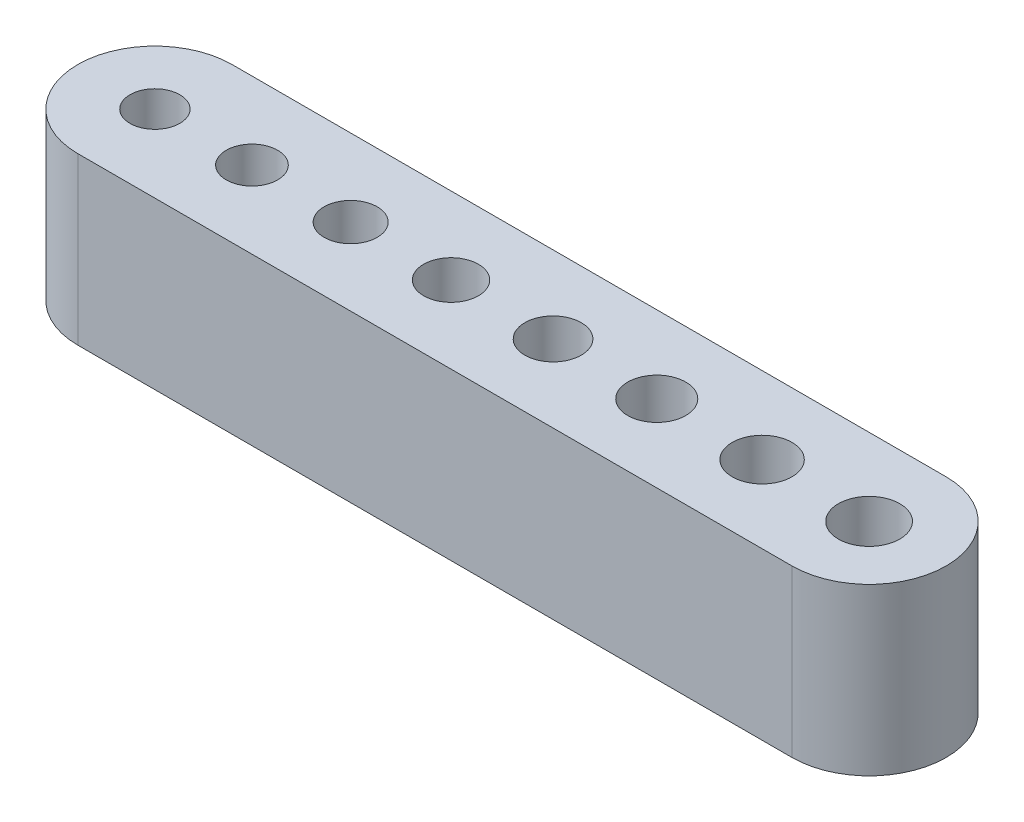
SolidWorks part; units mm, degrees
ref_plane "Front Plane" through (0, 0, 0) normal (0, 0, 1) x (1, 0, 0)
ref_plane "Top Plane" through (0, 0, 0) normal (0, 1, 0) x (1, 0, 0)
ref_plane "Right Plane" through (0, 0, 0) normal (1, 0, 0) x (0, 0, -1)
sketch "Sketch1" plane through (0, 0, 0) normal (0, 1, 0) x (1, 0, 0)
  line L0 (-21.525, 0) -> (21.525, 0) construction
  line L1 (-21.525, 4.65) -> (21.525, 4.65)
  line L2 (-21.525, -4.65) -> (21.525, -4.65)
  line L3 (-20.025, 0) -> (-17.225, 0) construction
  line L4 (-14.125, 0) -> (-11.325, 0) construction
  line L5 (-8.125, 0) -> (-5.325, 0) construction
  line L6 (-2.025, 0) -> (0.775, 0) construction
  line L7 (4.175, 0) -> (6.975, 0) construction
  line L8 (23.375, 0) -> (26.175, 0) construction
  line L10 (10.475, 0) -> (13.275, 0) construction
  line L11 (16.875, 0) -> (19.675, 0) construction
  arc A0 (-21.525, 4.65) -> (-21.525, -4.65) centre (-21.525, 0) ccw
  arc A1 (21.525, -4.65) -> (21.525, 4.65) centre (21.525, 0) ccw
  circle A2 centre (-21.525, 0) radius 1.5
  circle A3 centre (-15.675, 0) radius 1.55
  circle A4 centre (-9.725, 0) radius 1.6
  circle A5 centre (-3.675, 0) radius 1.65
  circle A6 centre (2.475, 0) radius 1.7
  circle A7 centre (21.525, 0) radius 1.85
  circle A8 centre (8.725, 0) radius 1.75
  circle A9 centre (15.075, 0) radius 1.8
  point P2 (0, 0)
  dimension "D1" = 3
  dimension "D2" = 3.1
  dimension "D3" = 3.2
  dimension "D4" = 3.3
  dimension "D5" = 3.4
  dimension "D6" = 3.7
  dimension "D7" = 3.5
  dimension "D8" = 3.6
  dimension "D9" = 2.8
extrude "Boss-Extrude1" add sketch "Sketch1" along normal blind 10
